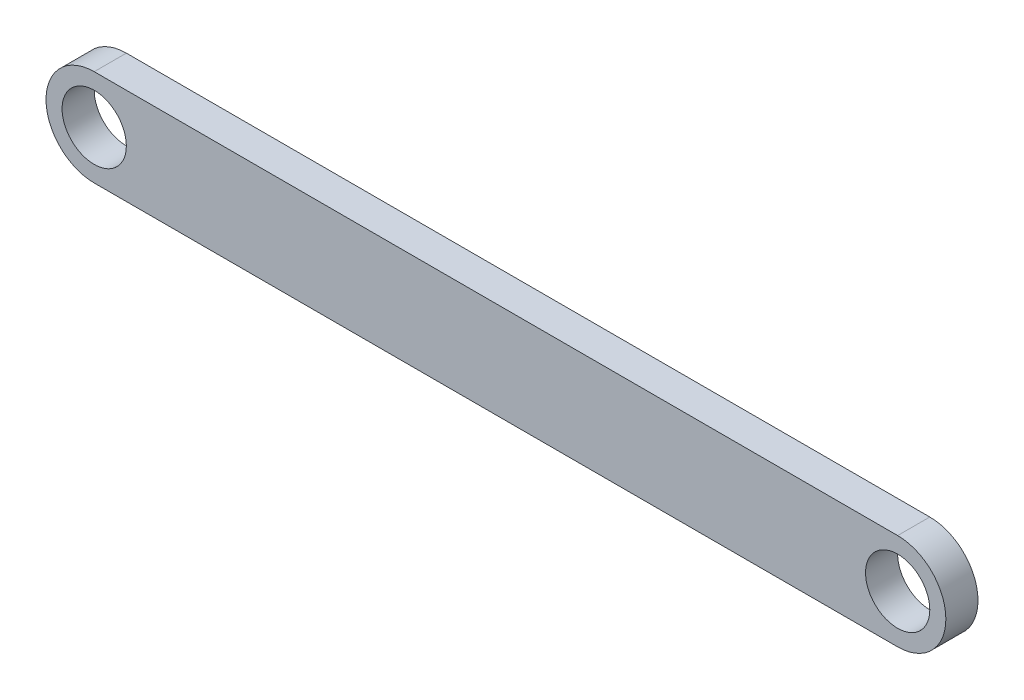
SolidWorks part; units mm, degrees
material "PVC Rigid"
ref_plane "Front Plane" through (0, 0, 0) normal (0, 0, 1) x (1, 0, 0)
ref_plane "Top Plane" through (0, 0, 0) normal (0, 1, 0) x (1, 0, 0)
ref_plane "Right Plane" through (0, 0, 0) normal (1, 0, 0) x (0, 0, -1)
sketch "Sketch1" plane through (0, 0, 0) normal (0, 0, 1) x (1, 0, 0)
  line L1 (-75.8515, 14.0552) -> (82.8985, 14.0552)
  line L3 (-75.8515, -4.9948) -> (82.8985, -4.9948)
  arc A0 (-75.8515, 14.0552) -> (-75.8515, -4.9948) centre (-75.8515, 4.5302) ccw
  arc A1 (82.8985, 14.0552) -> (82.8985, -4.9948) centre (82.8985, 4.5302) cw
  circle A2 centre (-75.8515, 4.5302) radius 6.35
  circle A3 centre (82.8985, 4.5302) radius 6.35
  point P7 (-85.3765, 4.5302)
  point P8 (92.4235, 4.5302)
  dimension "D2" = 177.8
  dimension "D1" = 19.05
extrude "Boss-Extrude1" add sketch "Sketch1" along normal blind 6.35
